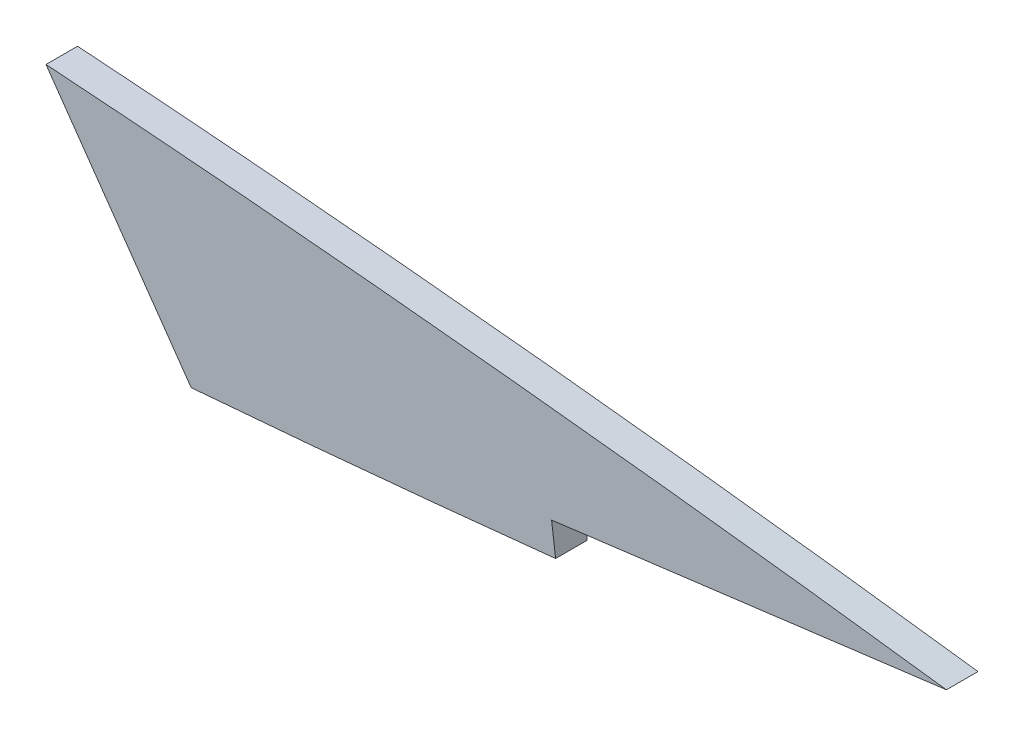
SolidWorks part; units mm, degrees
material "Balsa"
ref_plane "Front Plane" through (0, 0, 0) normal (0, 0, 1) x (1, 0, 0)
ref_plane "Top Plane" through (0, 0, 0) normal (0, 1, 0) x (1, 0, 0)
ref_plane "Right Plane" through (0, 0, 0) normal (1, 0, 0) x (0, 0, -1)
curve "Curve1"
  spline degree 3 poles (318.77, 0, 0) (318.6165, 0.178, 0) (318.1279, 0.7447, 0) (316.4159, 0.5798, 0) (314.0794, 1.1239, 0) (310.6457, 1.4976, 0) (306.3402, 2.1168, 0) (301.1057, 2.7975, 0) (295.0055, 3.5941, 0) (288.0665, 4.472, 0) (280.335, 5.4268, 0) (271.8575, 6.4421, 0) (262.6867, 7.5062, 0) (252.8789, 8.6045, 0) (242.4947, 9.7236, 0) (231.5982, 10.8496, 0) (220.2564, 11.9679, 0) (208.5394, 13.0629, 0) (196.5193, 14.1202, 0) (184.2704, 15.122, 0) (171.8679, 16.0521, 0) (159.3884, 16.8933, 0) (146.9087, 17.6278, 0) (134.5058, 18.2372, 0) (122.2562, 18.7052, 0) (110.2351, 19.0165, 0) (98.5168, 19.156, 0) (87.1732, 19.1125, 0) (76.2743, 18.8777, 0) (65.8873, 18.4456, 0) (56.076, 17.8151, 0) (46.9007, 16.9881, 0) (38.4176, 15.971, 0) (30.6784, 14.7725, 0) (23.7299, 13.4051, 0) (17.6134, 11.8842, 0) (12.3615, 10.2248, 0) (8.0073, 8.4423, 0) (4.5466, 6.5486, 0) (2.0351, 4.5401, 0) (0.333, 2.3682, 0) (0.1059, 0.7528, 0) (0, 0, 0) knots 0 0 0 0 0.002092 0.00666 0.01424 0.024785 0.038227 0.054481 0.073445 0.094999 0.119006 0.145319 0.17377 0.204184 0.236371 0.270129 0.30525 0.341517 0.378701 0.416575 0.454902 0.493447 0.531971 0.570237 0.608013 0.645066 0.681178 0.71613 0.749718 0.781748 0.812037 0.840415 0.866732 0.890849 0.912652 0.932046 0.948973 0.963413 0.975421 0.985175 0.993091 1 1 1 1
sketch "Sketch2" plane through (0, 0, 0) normal (0, 0, 1) x (1, 0, 0)
  line L4 (0, 0) -> (213.36, 0) construction
  spline S1 degree 3 poles (213.36, 0) (213.2573, 0.1191) (212.9302, 0.4985) (211.7843, 0.3881) (210.2205, 0.7522) (207.9222, 1.0024) (205.0404, 1.4168) (201.5369, 1.8724) (197.4539, 2.4056) (192.8094, 2.9932) (187.6346, 3.6323) (181.9604, 4.3118) (175.8222, 5.0241) (169.2576, 5.7592) (162.3072, 6.5082) (155.0139, 7.2619) (147.4226, 8.0104) (139.5802, 8.7433) (131.5349, 9.4509) (123.3364, 10.1215) (115.0351, 10.7441) (106.6823, 11.3071) (98.3294, 11.7987) (90.0278, 12.2066) (81.8289, 12.5198) (73.7829, 12.7282) (65.9395, 12.8215) (58.347, 12.7924) (51.0522, 12.6353) (44.0999, 12.3461) (37.5329, 11.9241) (31.3917, 11.3705) (25.7138, 10.6897) (20.5338, 9.8875) (15.8829, 8.9723) (11.789, 7.9544) (8.2739, 6.8437) (5.3595, 5.6506) (3.0432, 4.3831) (1.3621, 3.0388) (0.2229, 1.5851) (0.0709, 0.5039) (0, 0) knots 0 0 0 0 0.002092 0.00666 0.01424 0.024785 0.038227 0.054481 0.073445 0.094999 0.119006 0.145319 0.17377 0.204184 0.236371 0.270129 0.30525 0.341517 0.378701 0.416575 0.454902 0.493447 0.531971 0.570237 0.608013 0.645066 0.681178 0.71613 0.749718 0.781748 0.812037 0.840415 0.866732 0.890849 0.912652 0.932046 0.948973 0.963413 0.975421 0.985175 0.993091 1 1 1 1
  spline S2 degree 3 poles (213.36, 0) (213.2573, -0.1191) (212.9302, -0.4985) (211.7843, -0.3881) (210.2205, -0.7522) (207.9222, -1.0024) (205.0404, -1.4168) (201.5369, -1.8724) (197.4539, -2.4056) (192.8094, -2.9932) (187.6346, -3.6323) (181.9604, -4.3118) (175.8222, -5.0241) (169.2576, -5.7592) (162.3072, -6.5082) (155.0139, -7.2619) (147.4226, -8.0104) (139.5802, -8.7433) (131.5349, -9.4509) (123.3364, -10.1215) (115.0351, -10.7441) (106.6823, -11.3071) (98.3294, -11.7987) (90.0278, -12.2066) (81.8289, -12.5198) (73.7829, -12.7282) (65.9395, -12.8215) (58.347, -12.7924) (51.0522, -12.6353) (44.0999, -12.3461) (37.5329, -11.9241) (31.3917, -11.3705) (25.7138, -10.6897) (20.5338, -9.8875) (15.8829, -8.9723) (11.789, -7.9544) (8.2739, -6.8437) (5.3595, -5.6506) (3.0432, -4.3831) (1.3621, -3.0388) (0.2229, -1.5851) (0.0709, -0.5039) (0, 0) knots 0 0 0 0 0.002092 0.00666 0.01424 0.024785 0.038227 0.054481 0.073445 0.094999 0.119006 0.145319 0.17377 0.204184 0.236371 0.270129 0.30525 0.341517 0.378701 0.416575 0.454902 0.493447 0.531971 0.570237 0.608013 0.645066 0.681178 0.71613 0.749718 0.781748 0.812037 0.840415 0.866732 0.890849 0.912652 0.932046 0.948973 0.963413 0.975421 0.985175 0.993091 1 1 1 1
  dimension "D1" = 213.36
extrude "Boss-Extrude1" add sketch "Sketch2" along normal blind 3.175
sketch "Sketch3" plane through (0, 0, 3.175) normal (0, 0, 1) x (1, 0, 0)
  line L0 (0, 0) -> (111.76, 0) construction
  line L12 (111.76, 10.9617) -> (111.76, -10.9617) construction
  line L13 (111.76, 10.9617) -> (126.3482, -9.8724)
  line L14 (111.76, 10.9617) -> (111.76, 50.8)
  line L15 (111.76, 50.8) -> (0, 50.8)
  line L16 (0, 50.8) -> (0, 0)
  line L17 (0, 0) -> (0, -50.8)
  line L18 (0, -50.8) -> (126.3482, -50.8)
  line L19 (126.3482, -50.8) -> (126.3482, -9.8724)
  line L24 (163.371, -9.5824) -> (213.7621, -3.1494)
  line L25 (163.371, -9.5824) -> (162.5669, -3.2836)
  line L26 (213.7621, -3.1494) -> (212.9579, 3.1494)
  line L27 (162.5669, -3.2836) -> (212.9579, 3.1494)
  spline S0 degree 3 poles (-944.2723, -328.7736) (44.0548, 37.616) (-6.2052, 6.6173) (1.3621, -3.0388) (3.0432, -4.3831) (5.3595, -5.6506) (8.2739, -6.8437) (11.789, -7.9544) (15.8829, -8.9723) (20.5338, -9.8875) (25.7138, -10.6897) (31.3917, -11.3705) (37.5329, -11.9241) (44.0999, -12.3461) (51.0522, -12.6353) (58.347, -12.7924) (65.9395, -12.8215) (73.7829, -12.7282) (81.8289, -12.5198) (90.0278, -12.2066) (98.3294, -11.7987) (106.6823, -11.3071) (115.0351, -10.7441) (123.3364, -10.1215) (131.5349, -9.4509) (139.5802, -8.7433) (147.4226, -8.0104) (155.0139, -7.2619) (162.3072, -6.5082) (169.2576, -5.7592) (175.8222, -5.0241) (181.9604, -4.3118) (187.6346, -3.6323) (192.8094, -2.9932) (197.4539, -2.4056) (201.5369, -1.8724) (205.0404, -1.4168) (207.9222, -1.0024) (210.2205, -0.7522) (211.7843, -0.3881) (217.5939, -0.9477) (203.1323, 39.1175) (660.1213, -894.2583) knots -0.138684 -0.138684 -0.138684 -0.138684 0.006909 0.014825 0.024579 0.036587 0.051027 0.067954 0.087348 0.109151 0.133268 0.159585 0.187963 0.218252 0.250282 0.28387 0.318822 0.354934 0.391987 0.429763 0.468029 0.506553 0.545098 0.583425 0.621299 0.658483 0.69475 0.729871 0.763629 0.795816 0.82623 0.854681 0.880994 0.905001 0.926555 0.945519 0.961773 0.975215 0.98576 0.99334 0.997908 1.057956 1.057956 1.057956 1.057956 only from (0, 0) to (213.36, 0) construction
  spline S1 degree 3 poles (660.1929, 894.4045) (203.1309, -39.1214) (217.5942, 0.9477) (211.7843, 0.3881) (210.2205, 0.7522) (207.9222, 1.0024) (205.0404, 1.4168) (201.5369, 1.8724) (197.4539, 2.4056) (192.8094, 2.9932) (187.6346, 3.6323) (181.9604, 4.3118) (175.8222, 5.0241) (169.2576, 5.7592) (162.3072, 6.5082) (155.0139, 7.2619) (147.4226, 8.0104) (139.5802, 8.7433) (131.5349, 9.4509) (123.3364, 10.1215) (115.0351, 10.7441) (106.6823, 11.3071) (98.3294, 11.7987) (90.0278, 12.2066) (81.8289, 12.5198) (73.7829, 12.7282) (65.9395, 12.8215) (58.347, 12.7924) (51.0522, 12.6353) (44.0999, 12.3461) (37.5329, 11.9241) (31.3917, 11.3705) (25.7138, 10.6897) (20.5338, 9.8875) (15.8829, 8.9723) (11.789, 7.9544) (8.2739, 6.8437) (5.3595, 5.6506) (3.0432, 4.3831) (1.3621, 3.0388) (-6.2052, -6.6172) (44.0539, -37.6155) (-944.2455, 328.7637) knots -0.057959 -0.057959 -0.057959 -0.057959 0.002092 0.00666 0.01424 0.024785 0.038227 0.054481 0.073445 0.094999 0.119006 0.145319 0.17377 0.204184 0.236371 0.270129 0.30525 0.341517 0.378701 0.416575 0.454902 0.493447 0.531971 0.570237 0.608013 0.645066 0.681178 0.71613 0.749718 0.781748 0.812037 0.840415 0.866732 0.890849 0.912652 0.932046 0.948973 0.963413 0.975421 0.985175 0.993091 1.138683 1.138683 1.138683 1.138683 only from (213.36, 0) to (0, 0) construction
  spline S2 degree 3 poles (111.76, -10.9617) (112.8568, -10.887) (116.7273, -10.6172) (123.3364, -10.1215) (131.5349, -9.4509) (139.5802, -8.7433) (147.4226, -8.0104) (155.0139, -7.2619) (162.3072, -6.5082) (169.2576, -5.7592) (175.8222, -5.0241) (181.9604, -4.3118) (187.6346, -3.6323) (192.8094, -2.9932) (197.4539, -2.4056) (201.5369, -1.8724) (205.0404, -1.4168) (207.9222, -1.0024) (210.2205, -0.7522) (211.7843, -0.3881) (212.9302, -0.4985) (213.2573, -0.1191) (213.36, 0) knots 0.529944 0.529944 0.529944 0.529944 0.545098 0.583425 0.621299 0.658483 0.69475 0.729871 0.763629 0.795816 0.82623 0.854681 0.880994 0.905001 0.926555 0.945519 0.961773 0.975215 0.98576 0.99334 0.997908 1 1 1 1 construction
  spline S3 degree 3 poles (213.36, 0) (213.2573, 0.1191) (212.9302, 0.4985) (211.7843, 0.3881) (210.2205, 0.7522) (207.9222, 1.0024) (205.0404, 1.4168) (201.5369, 1.8724) (197.4539, 2.4056) (192.8094, 2.9932) (187.6346, 3.6323) (181.9604, 4.3118) (175.8222, 5.0241) (169.2576, 5.7592) (162.3072, 6.5082) (155.0139, 7.2619) (147.4226, 8.0104) (139.5802, 8.7433) (131.5349, 9.4509) (123.3364, 10.1215) (116.7273, 10.6172) (112.8568, 10.887) (111.76, 10.9617) knots 0 0 0 0 0.002092 0.00666 0.01424 0.024785 0.038227 0.054481 0.073445 0.094999 0.119006 0.145319 0.17377 0.204184 0.236371 0.270129 0.30525 0.341517 0.378701 0.416575 0.454902 0.470056 0.470056 0.470056 0.470056 construction
  point P3 (162.969, -6.433)
  dimension "D5" = 50.8
  dimension "D1" = 50.8
  dimension "D2" = 101.6
  dimension "D3" = 35
  dimension "D4" = 50.8
  dimension "D6" = 6.35
extrude "Cut-Extrude1" cut sketch "Sketch3" against normal blind 5.08
ref_plane "Adjusted Right Plane" through (111.76, 0, 0) normal (1, 0, 0) x (0, 0, -1)
